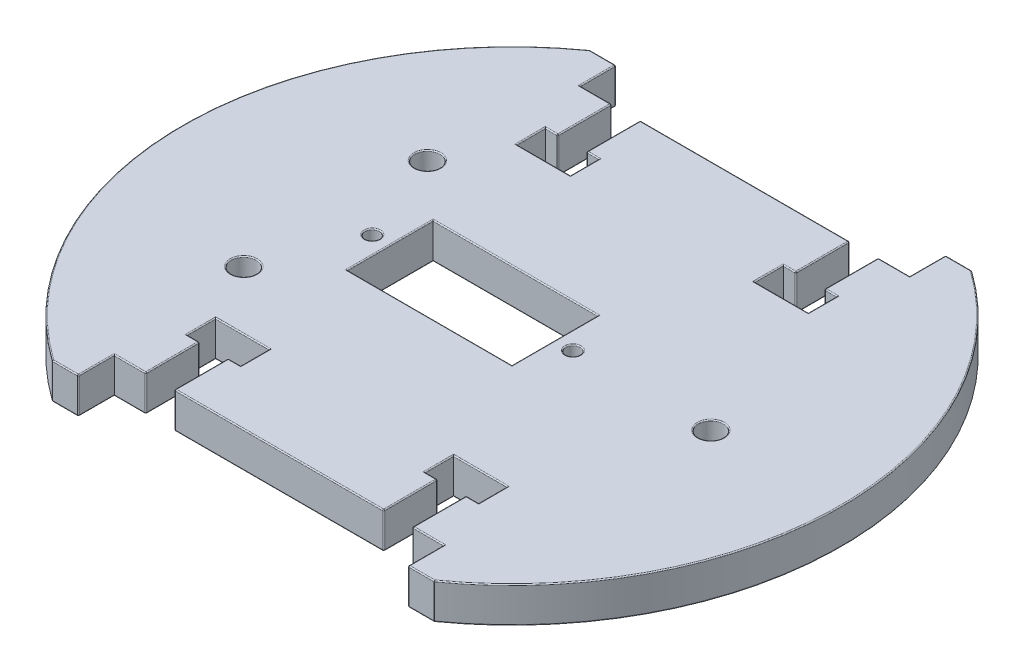
SolidWorks part; units mm, degrees
ref_plane "前视基准面" through (0, 0, 0) normal (0, 0, 1) x (1, 0, 0)
ref_plane "上视基准面" through (0, 0, 0) normal (0, 1, 0) x (1, 0, 0)
ref_plane "右视基准面" through (0, 0, 0) normal (1, 0, 0) x (0, 0, -1)
sketch "草图1" plane through (0, 0, 0) normal (0, 1, 0) x (1, 0, 0)
  line L0 (-26.6411, 37.5) -> (-23, 37.5)
  line L1 (23, 37.5) -> (26.6411, 37.5)
  line L3 (-23, 37.5) -> (-23, 32.5)
  line L4 (-23, 32.5) -> (23, 32.5)
  line L5 (23, 37.5) -> (23, 32.5)
  line L6 (0, 0) -> (-46, 0) construction
  line L7 (-26.6411, -37.5) -> (-23, -37.5)
  line L8 (23, -37.5) -> (26.6411, -37.5)
  line L9 (-23, -37.5) -> (-23, -32.5)
  line L10 (23, -37.5) -> (23, -32.5)
  line L11 (-23, -32.5) -> (23, -32.5)
  line L13 (-17, -6) -> (6, -6)
  line L14 (-17, -6) -> (-17, 6)
  line L15 (-17, 6) -> (6, 6)
  line L16 (6, -6) -> (6, 6)
  line L17 (-17, -6) -> (6, 6) construction
  line L18 (-17, 6) -> (6, -6) construction
  line L19 (-24.6146, 12.8135) -> (-24.6146, -12.8135) construction
  line L20 (-24.6146, 12.8135) -> (0, 0) construction
  line L21 (0, 0) -> (4.0097, 1.022) construction
  line L22 (0, 0) -> (-24.6146, -12.8135) construction
  arc A0 (-26.6411, 37.5) -> (-26.6411, -37.5) centre (0, 0) ccw
  arc A1 (26.6411, -37.5) -> (26.6411, 37.5) centre (0, 0) ccw
  circle A2 centre (-19.5, 0) radius 1
  circle A3 centre (8.5, 0) radius 1
  circle A4 centre (-24.6146, 12.8135) radius 1.75
  circle A5 centre (-24.6146, -12.8135) radius 1.75
  circle A6 centre (27.7487, 0) radius 1.75
  point P14 (0, 32.5)
  point P16 (-5.5, 0)
  point P23 (6, 0)
  point P26 (-17, 0)
  dimension "D1" = 92
  dimension "D8" = 2
  dimension "D11" = 2
  dimension "D17" = 3.5
  dimension "D2" = 37.5
  dimension "D3" = 46
  dimension "D4" = 5
  dimension "D5" = 23
  dimension "D6" = 12
  dimension "D7" = 6
  dimension "D9" = 2.5
  dimension "D10" = 2.5
  dimension "D12" = 55
  dimension "D13" = 27.7487
  dimension "D15" = 27.75
  dimension "D16" = 32.5
extrude "凸台-拉伸1" add sketch "草图1" along normal blind 5
sketch "草图3" plane through (0, 5, 0) normal (0, 1, 0) x (1, 0, 0)
  line L0 (23, 32.5) -> (-23, 32.5) construction
  line L1 (-14.6, 25) -> (-18.6, 25)
  line L2 (-14.6, 25) -> (-14.6, 32.5)
  line L3 (-14.6, 32.5) -> (-18.6, 32.5)
  line L4 (-18.6, 25) -> (-18.6, 32.5)
  line L5 (-14.6, 25) -> (-18.6, 32.5) construction
  line L6 (-14.6, 32.5) -> (-18.6, 25) construction
  line L8 (-20.35, 21) -> (-12.85, 21)
  line L9 (-20.35, 21) -> (-20.35, 25)
  line L10 (-20.35, 25) -> (-12.85, 25)
  line L11 (-12.85, 21) -> (-12.85, 25)
  line L12 (-20.35, 21) -> (-12.85, 25) construction
  line L13 (-20.35, 25) -> (-12.85, 21) construction
  line L14 (-17, 0) -> (0, 0) construction
  line L15 (-17, 6) -> (-17, -6) construction
  line L16 (0, 0) -> (0, 32.5) construction
  line L17 (20.35, 25) -> (12.85, 21) construction
  line L18 (20.35, 21) -> (12.85, 25) construction
  line L19 (14.6, 32.5) -> (18.6, 25) construction
  line L20 (14.6, 25) -> (18.6, 32.5) construction
  line L21 (12.85, 21) -> (12.85, 25)
  line L22 (20.35, 25) -> (12.85, 25)
  line L23 (20.35, 21) -> (20.35, 25)
  line L24 (20.35, 21) -> (12.85, 21)
  line L25 (18.6, 25) -> (18.6, 32.5)
  line L26 (14.6, 32.5) -> (18.6, 32.5)
  line L27 (14.6, 25) -> (14.6, 32.5)
  line L28 (14.6, 25) -> (18.6, 25)
  line L29 (-18.6, -25) -> (-18.6, -32.5)
  line L30 (-14.6, -32.5) -> (-18.6, -32.5)
  line L31 (-14.6, -25) -> (-14.6, -32.5)
  line L32 (14.6, -32.5) -> (18.6, -32.5)
  line L33 (14.6, -25) -> (14.6, -32.5)
  line L34 (18.6, -25) -> (18.6, -32.5)
  line L35 (20.35, -21) -> (12.85, -25) construction
  line L36 (20.35, -25) -> (12.85, -21) construction
  line L37 (-20.35, -25) -> (-12.85, -21) construction
  line L38 (-20.35, -21) -> (-12.85, -25) construction
  line L39 (14.6, -25) -> (18.6, -25)
  line L40 (20.35, -21) -> (12.85, -21)
  line L41 (20.35, -21) -> (20.35, -25)
  line L42 (20.35, -25) -> (12.85, -25)
  line L43 (12.85, -21) -> (12.85, -25)
  line L44 (-12.85, -21) -> (-12.85, -25)
  line L45 (-20.35, -25) -> (-12.85, -25)
  line L46 (-20.35, -21) -> (-20.35, -25)
  line L47 (-20.35, -21) -> (-12.85, -21)
  line L48 (-14.6, -25) -> (-18.6, -25)
  line L49 (-24.6146, -12.8135) -> (0, 0) construction
  line L50 (0, 0) -> (27.7487, 0) construction
  line L51 (0, 0) -> (-24.6146, 12.8135) construction
  line L52 (-23, 32.5) -> (-23, 37.5) construction
  line L53 (-61.5814, -20.1363) -> (-61.5814, -19.6331) construction
  point P0 (-16.6, 28.75)
  point P7 (-16.6, 23)
  point P28 (16.6, 23)
  point P29 (16.6, 28.75)
  point P46 (16.6, -28.75)
  point P47 (16.6, -23)
  point P48 (-16.6, -23)
  point P49 (-16.6, -28.75)
  dimension "D1" = 6.4
  dimension "D2" = 4
  dimension "D3" = 7.5
  dimension "D4" = 4
  dimension "D5" = 7.5
extrude "切除-拉伸1" cut sketch "草图3" against normal through all contours L4 L3 L2 L1 | L9 L10 L11 L8 | L27 L26 L25 L28 | L21 L22 L23 L24 | L46 L45 L44 L47 | L29 L30 L31 L48 | L33 L32 L34 L39 | L43 L42 L41 L40
fillet "圆角1" radius 0.15 130 edges at (-18.6, 2.5, -25) (-18.6, 2.5, -32.5) (-14.6, 2.5, -32.5) (-14.6, 2.5, -25) (-14.6, 0, -28.75) (-18.6, 0, -28.75) (-14.6, 5, -28.75) (-18.6, 5, -28.75) (-20.35, 0, -23) (-19.475, 0, -25) (-13.725, 0, -25) (-12.85, 0, -23) (-16.6, 0, -21) (-20.35, 5, -23) (-19.475, 5, -25) (-13.725, 5, -25) (-12.85, 5, -23) (-16.6, 5, -21) (-14.6, 2.5, 25) (-18.6, 2.5, 25) (-20.35, 0, 23) (-19.475, 0, 25) (-13.725, 0, 25) (-12.85, 0, 23) (-16.6, 0, 21) (-20.35, 5, 23) (-19.475, 5, 25) (-13.725, 5, 25) (-12.85, 5, 23) (-16.6, 5, 21) (-14.6, 2.5, 32.5) (-18.6, 2.5, 32.5) (-14.6, 0, 28.75) (-18.6, 0, 28.75) (-14.6, 5, 28.75) (-18.6, 5, 28.75) (18.6, 2.5, 25) (18.6, 2.5, 32.5) (14.6, 2.5, 25) (14.6, 0, 28.75) (18.6, 0, 28.75) (14.6, 5, 28.75) (18.6, 5, 28.75) (20.35, 0, 23) (19.475, 0, 25) (13.725, 0, 25) (12.85, 0, 23) (16.6, 0, 21) (20.35, 5, 23) (19.475, 5, 25) (13.725, 5, 25) (12.85, 5, 23) (16.6, 5, 21) (16.6, 5, -21) (12.85, 5, -23) (13.725, 5, -25) (19.475, 5, -25) (20.35, 5, -23) (16.6, 0, -21) (12.85, 0, -23) (13.725, 0, -25) (19.475, 0, -25) (20.35, 0, -23) (18.6, 5, -28.75) (14.6, 5, -28.75) (18.6, 0, -28.75) (14.6, 0, -28.75) (18.6, 2.5, -25) (18.6, 2.5, -32.5) (14.6, 2.5, -32.5) (14.6, 2.5, -25) (-24.6146, 0, -11.0635) (-24.6146, 5, -11.0635) (27.7487, 0, 1.75) (27.7487, 5, 1.75) (-24.6146, 0, 14.5635) (-24.6146, 5, 14.5635) (-19.5, 0, 1) (-19.5, 5, 1) (8.5, 0, 1) (8.5, 5, 1) (6, 0, 0) (-5.5, 0, -6) (-17, 0, 0) (-5.5, 0, 6) (6, 5, 0) (-5.5, 5, -6) (-17, 5, 0) (-5.5, 5, 6) (-46, 0, 0) (-24.8206, 0, 37.5) (-23, 0, 35) (20.8, 0, 32.5) (0, 0, 32.5) (-20.8, 0, 32.5) (23, 0, 35) (24.8206, 0, 37.5) (46, 0, 0) (24.8206, 0, -37.5) (23, 0, -35) (-20.8, 0, -32.5) (0, 0, -32.5) (20.8, 0, -32.5) (-23, 0, -35) (-24.8206, 0, -37.5) (-46, 5, 0) (-24.8206, 5, 37.5) (-23, 5, 35) (20.8, 5, 32.5) (0, 5, 32.5) (-20.8, 5, 32.5) (23, 5, 35) (24.8206, 5, 37.5) (46, 5, 0) (24.8206, 5, -37.5) (23, 5, -35) (-20.8, 5, -32.5) (0, 5, -32.5) (20.8, 5, -32.5) (-23, 5, -35) (-24.8206, 5, -37.5) (-26.6411, 2.5, -37.5) (-23, 2.5, -37.5) (23, 2.5, -37.5) (26.6411, 2.5, -37.5) (26.6411, 2.5, 37.5) (23, 2.5, 37.5) (-23, 2.5, 37.5) (-26.6411, 2.5, 37.5) (14.6, 2.5, 32.5)
